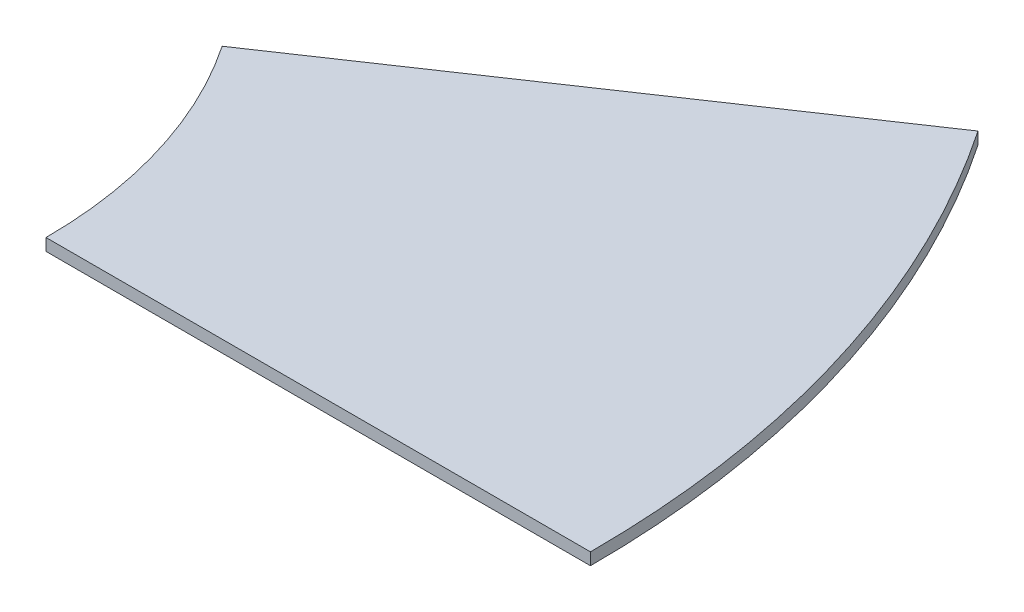
SolidWorks part; units mm, degrees
ref_plane "Front" through (0, 0, 0) normal (0, 0, 1) x (1, 0, 0)
ref_plane "Top" through (0, 0, 0) normal (0, 1, 0) x (1, 0, 0)
ref_plane "Right" through (0, 0, 0) normal (1, 0, 0) x (0, 0, -1)
sketch "草图1" plane through (0, 0, 0) normal (0, 1, 0) x (1, 0, 0)
  line L0 (0, 0) -> (110, 0) construction
  line L1 (91.1941, 61.5112) -> (0, 0) construction
  line L2 (91.1941, 61.5112) -> (41.4519, 27.9596)
  line L3 (110, 0) -> (50, 0)
  arc A0 (110, 0) -> (91.1941, 61.5112) centre (0, 0) ccw
  arc A1 (50, 0) -> (41.4519, 27.9596) centre (0, 0) ccw
  dimension "D2" = 50
  dimension "D3" = 110
  dimension "D1" = 34
extrude "凸台-拉伸1" add sketch "草图1" along normal blind 1.33 contours L3 A1 L2 A0
